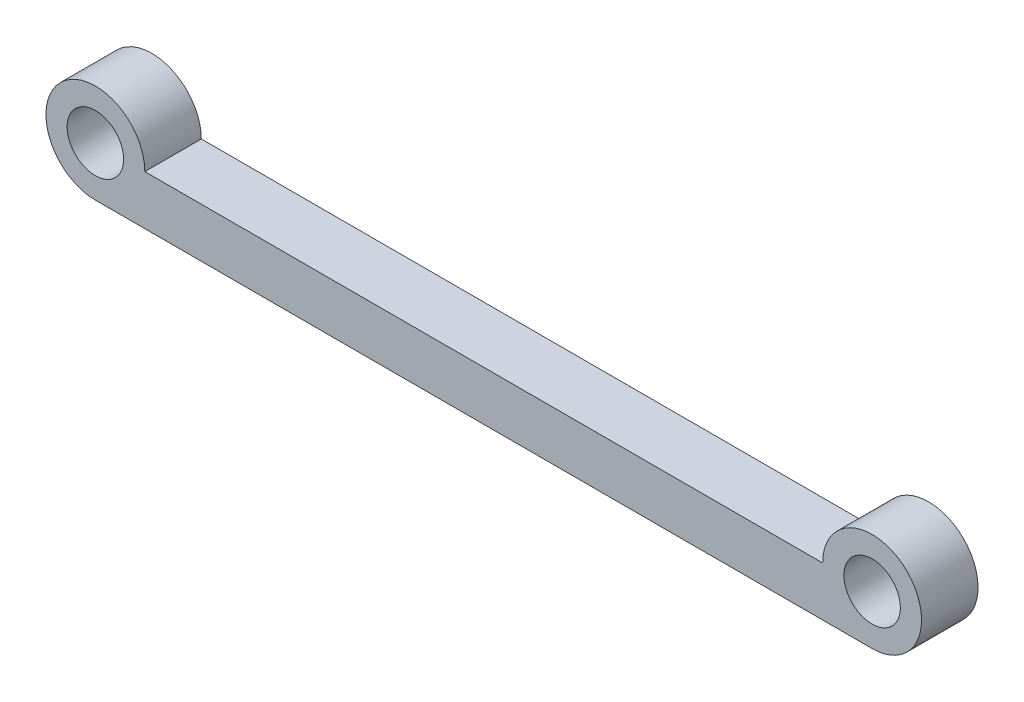
SolidWorks part; units mm, degrees
ref_plane "正面" through (0, 0, 0) normal (0, 0, 1) x (1, 0, 0)
ref_plane "平面" through (0, 0, 0) normal (0, 1, 0) x (1, 0, 0)
ref_plane "右側面" through (0, 0, 0) normal (1, 0, 0) x (0, 0, -1)
sketch "ｽｹｯﾁ1" plane through (0, 0, 0) normal (0, 0, 1) x (1, 0, 0)
  line L0 (0, -3.5) -> (55, -3.5)
  line L1 (3.5, 0) -> (51.5, 0)
  arc A0 (3.5, 0) -> (0, -3.5) centre (0, 0) ccw
  arc A1 (55, -3.5) -> (51.5, 0) centre (55, 0) ccw
  circle A2 centre (0, 0) radius 2
  circle A3 centre (55, 0) radius 2
  point P10 (0, 0)
  point P12 (3.5, 0)
  point P13 (49.6168, 3.5)
  dimension "D3" = 7
  dimension "D4" = 7
  dimension "D2" = 4
  dimension "D5" = 4
  dimension "D1" = 55
extrude "ﾎﾞｽ - 押し出し1" add sketch "ｽｹｯﾁ1" along normal blind 4
